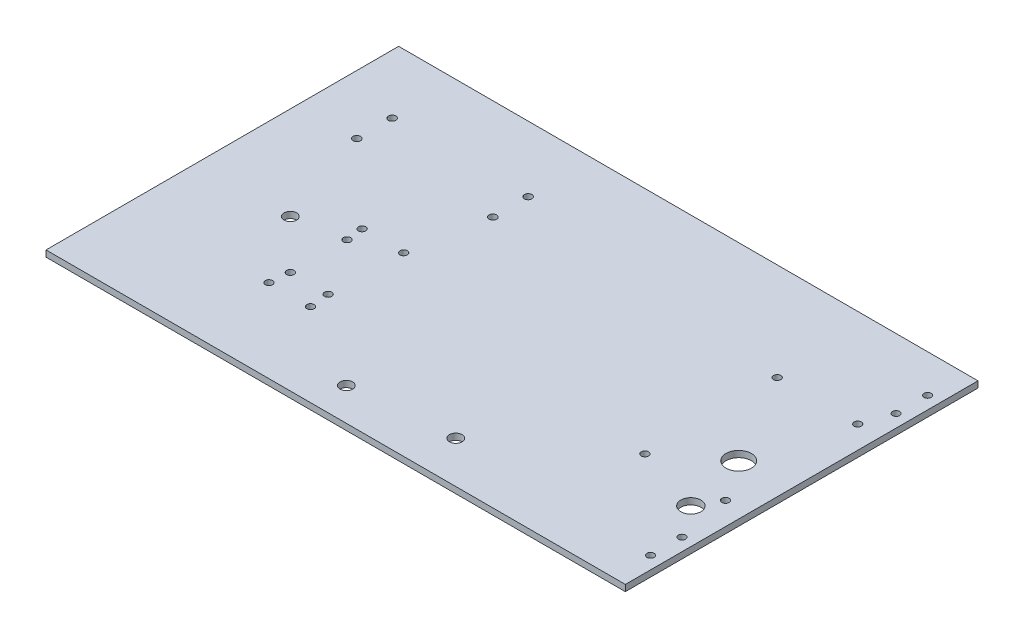
SolidWorks part; units mm, degrees
ref_plane "Front Plane" through (0, 0, 0) normal (0, 0, 1) x (1, 0, 0)
ref_plane "Top Plane" through (0, 0, 0) normal (0, 1, 0) x (1, 0, 0)
ref_plane "Right Plane" through (0, 0, 0) normal (1, 0, 0) x (0, 0, -1)
sketch "Sketch1" plane through (0, 0, 0) normal (0, 1, 0) x (1, 0, 0)
  line L1 (-158.75, 88.9) -> (158.75, 88.9)
  line L2 (-158.75, 88.9) -> (-158.75, -88.9)
  line L3 (-158.75, -88.9) -> (158.75, -88.9)
  line L4 (158.75, 88.9) -> (158.75, -88.9)
  line L5 (-158.75, 88.9) -> (158.75, -88.9) construction
  line L6 (-158.75, -88.9) -> (158.75, 88.9) construction
  circle A0 centre (-111.76, -12.7) radius 3.175
  circle A1 centre (107.95, -6.35) radius 6.4135
  circle A4 centre (-129.032, 55.88) radius 1.905
  circle A5 centre (-60.452, 55.88) radius 1.905
  circle A7 centre (-129.032, 38.1) radius 1.905
  circle A8 centre (-60.452, 38.1) radius 1.905
  point P0 (0, 0)
  dimension "D3" = 6.35
  dimension "D4" = 12.827
  dimension "D14" = 3.81
  dimension "D17" = 17.78
  dimension "D1" = 317.5
  dimension "D2" = 177.8
  dimension "D5" = 46.99
  dimension "D6" = 266.7
  dimension "D7" = 95.25
  dimension "D8" = 76.2
  dimension "D13" = 29.718
  dimension "D15" = 68.58
  dimension "D16" = 127
extrude "Boss-Extrude1" add sketch "Sketch1" along normal blind 3.175
sketch "Sketch2" plane through (0, 3.175, 0) normal (0, 1, 0) x (1, 0, 0)
  line L0 (-158.75, 88.9) -> (-158.75, -88.9) construction
  line L1 (-158.75, -88.9) -> (158.75, -88.9) construction
  circle A0 centre (-89.0817, -33.177) radius 1.905
  circle A1 centre (-132.1376, -36.4483) radius 1.905
  dimension "D1" = 3.81
  dimension "D2" = 69.6683
  dimension "D3" = 52.4517
  dimension "D4" = 55.723
  dimension "D5" = 43.18
extrude "Cut-Extrude1" [suppressed] cut sketch "Sketch2" against normal through all
sketch "Sketch3" plane through (0, 0, 0) normal (0, -1, 0) x (-1, 0, 0)
  line L0 (158.75, -88.9) -> (-158.75, -88.9) construction
  line L1 (158.75, 88.9) -> (158.75, -88.9) construction
  circle A0 centre (23.8295, -72.39) radius 3.175
  circle A1 centre (-26.7643, -67.818) radius 3.175
  dimension "D1" = 6.35
  dimension "D2" = 4.572
  dimension "D3" = 16.51
  dimension "D4" = 185.5143
  dimension "D5" = 50.8
extrude "Cut-Extrude2" cut sketch "Sketch3" against normal through all
sketch "Sketch4" plane through (0, 3.175, 0) normal (0, 1, 0) x (1, 0, 0)
  line L0 (-158.75, -88.9) -> (158.75, -88.9) construction
  line L1 (158.75, 88.9) -> (133.35, 88.9)
  line L2 (158.75, 88.9) -> (158.75, -88.9)
  line L3 (158.75, -88.9) -> (133.35, -88.9)
  line L4 (133.35, 88.9) -> (133.35, -88.9)
  dimension "D1" = 25.4
extrude "Cut-Extrude3" cut sketch "Sketch4" against normal through all
sketch "Sketch5" plane through (0, 3.175, 0) normal (0, 1, 0) x (1, 0, 0)
  line L0 (133.35, 88.9) -> (-158.75, 88.9) construction
  line L1 (133.35, 88.9) -> (133.35, -88.9) construction
  circle A0 centre (115.57, -38.1) radius 5.08
  dimension "D3" = 10.16
  dimension "D1" = 127
  dimension "D2" = 17.78
extrude "Cut-Extrude4" cut sketch "Sketch5" against normal through all
sketch "Sketch6" plane through (0, 0, 0) normal (0, -1, 0) x (1, 0, 0)
  line L0 (-158.75, 88.9) -> (133.35, 88.9) construction
  line L1 (133.35, -88.9) -> (133.35, 88.9) construction
  line L2 (133.35, -88.9) -> (-158.75, -88.9) construction
  circle A0 centre (127, 69.85) radius 1.8034
  circle A2 centre (127, 53.975) radius 1.8034
  circle A3 centre (127, -53.975) radius 1.8034
  circle A4 centre (127, -69.85) radius 1.8034
  dimension "D4" = 3.6068
  dimension "D5" = 6.35
  dimension "D1" = 15.875
  dimension "D2" = 19.05
  dimension "D3" = 6.35
  dimension "D6" = 15.875
  dimension "D7" = 19.05
extrude "Cut-Extrude5" cut sketch "Sketch6" against normal through all
sketch "Sketch7" plane through (0, 3.175, 0) normal (0, 1, 0) x (1, 0, 0)
  line L0 (133.35, 88.9) -> (133.35, -88.9) construction
  line L1 (133.35, 88.9) -> (-158.75, 88.9) construction
  line L2 (-158.75, 88.9) -> (-158.75, -88.9) construction
  circle A1 centre (121.92, 39.6875) radius 1.8415
  circle A2 centre (81.28, 39.6875) radius 1.8415
  circle A3 centre (81.28, -26.9875) radius 1.8415
  circle A4 centre (121.92, -26.9875) radius 1.8415
  circle A5 centre (-88.265, -46.99) radius 1.8415
  circle A6 centre (-67.31, -46.99) radius 1.8415
  circle A7 centre (-87.3125, -37.1475) radius 1.8415
  circle A8 centre (-68.2625, -37.1475) radius 1.8415
  circle A9 centre (-87.3125, -8.5725) radius 1.8415
  circle A10 centre (-88.265, 0) radius 1.8415
  circle A11 centre (-67.31, 0) radius 1.8415
  dimension "D1" = 11.43
  dimension "D5" = 3.683
  dimension "D10" = 3.683
  dimension "D15" = 3.683
  dimension "D2" = 40.64
  dimension "D3" = 66.675
  dimension "D4" = 49.2125
  dimension "D6" = 70.485
  dimension "D7" = 20.955
  dimension "D8" = 71.4375
  dimension "D9" = 19.05
  dimension "D11" = 88.9
  dimension "D12" = 8.5725
  dimension "D13" = 28.575
  dimension "D14" = 9.8425
extrude "Cut-Extrude6" cut sketch "Sketch7" against normal through all
